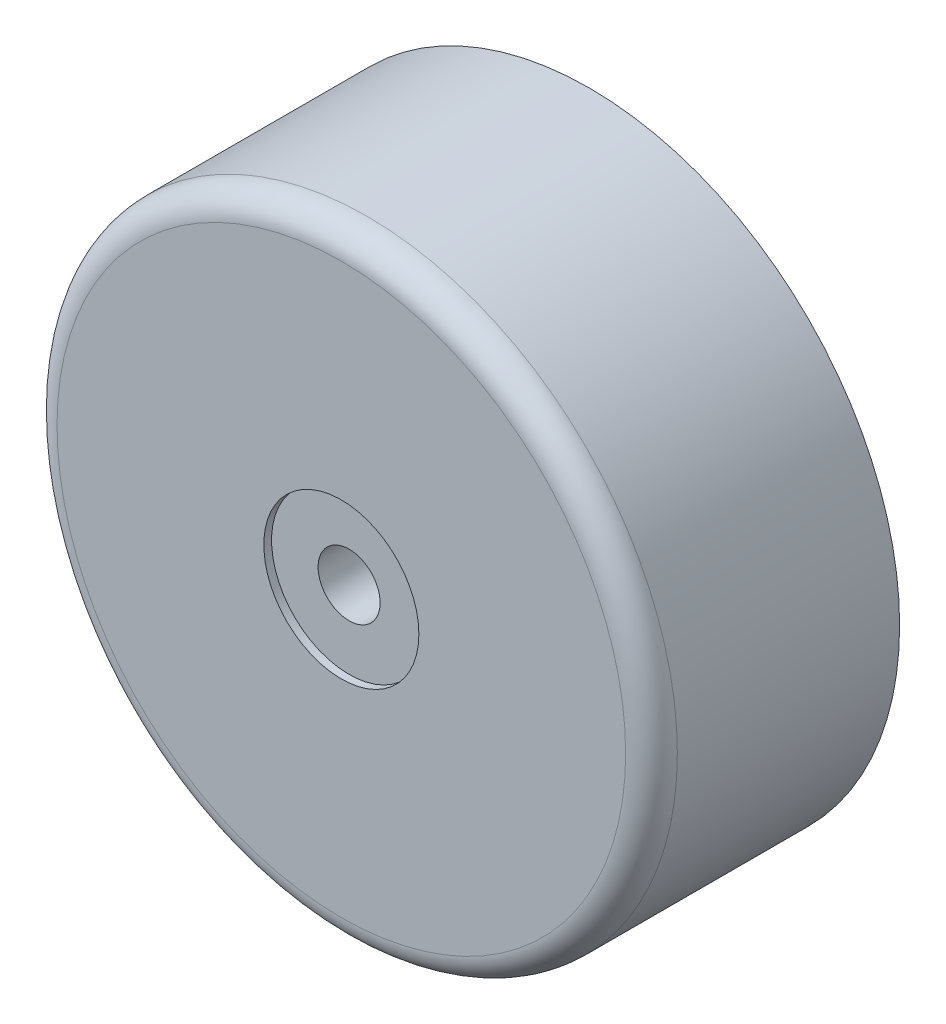
SolidWorks part; units mm, degrees
ref_plane "Frontal" through (0, 0, 0) normal (0, 0, 1) x (1, 0, 0)
ref_plane "Superior" through (0, 0, 0) normal (0, 1, 0) x (1, 0, 0)
ref_plane "Direito" through (0, 0, 0) normal (1, 0, 0) x (0, 0, -1)
sketch "Esboço1" plane through (0, 0, 0) normal (0, 0, 1) x (1, 0, 0)
  circle A0 centre (0, 0) radius 12
  dimension "D1" = 24
extrude "Ressalto-extrusão1" add sketch "Esboço1" along normal blind 9.6
sketch "Esboço2" plane through (0, 0, 0) normal (0, 0, -1) x (-1, 0, 0)
  circle A0 centre (0, 0) radius 11.4
  circle A1 centre (0, 0) radius 12
  circle A2 centre (0, 0) radius 12 construction
  dimension "D1" = 0
  dimension "D2" = 0.6
extrude "Corte-extrusão1" cut sketch "Esboço2" against normal blind 0.1
sketch "Esboço3" plane through (0, 0, 0.1) normal (0, 0, -1) x (-1, 0, 0)
  line L0 (0, 0) -> (6, 0) construction
  line L1 (6, 0) -> (-6, 0) construction
  circle A0 centre (6, 0) radius 0.5
  circle A1 centre (-6, 0) radius 0.5
  dimension "D1" = 12
  dimension "D2" = 6
extrude "Ressalto-extrusão2" add sketch "Esboço3" along normal blind 2
sketch "Esboço4" plane through (0, 0, 9.6) normal (0, 0, 1) x (1, 0, 0)
  circle A0 centre (0, 0) radius 1.2
extrude "Corte-extrusão2" cut sketch "Esboço4" against normal blind 2
sketch "Esboço5" plane through (0, 0, 9.6) normal (0, 0, 1) x (1, 0, 0)
  circle A0 centre (0, 0) radius 3
extrude "Corte-extrusão3" cut sketch "Esboço5" against normal blind 0.3
fillet "Filete1" radius 1 1 edges at (12, 0, 9.6)
